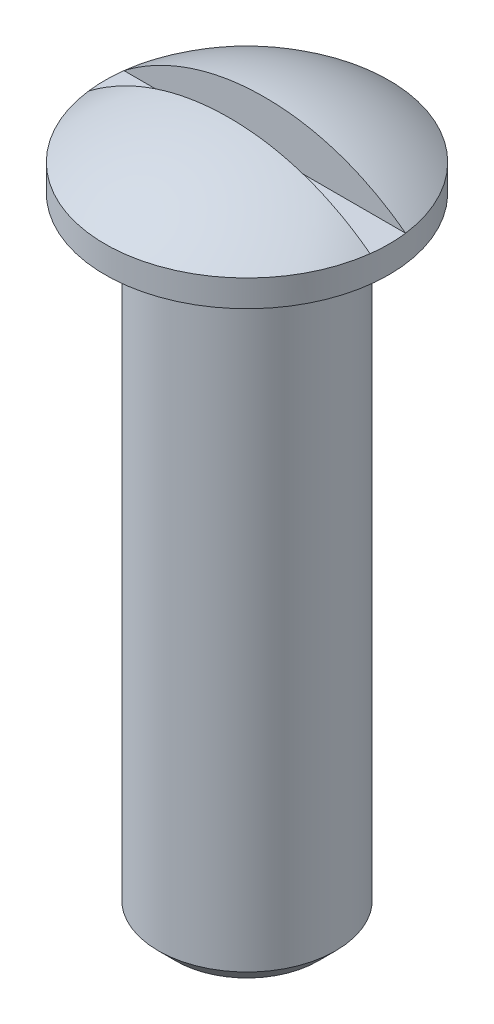
SolidWorks part; units mm, degrees
material "1.0503 (C45)"
ref_plane "Płaszczyzna przednia" through (0, 0, 0) normal (0, 0, 1) x (1, 0, 0)
ref_plane "Płaszczyzna górna" through (0, 0, 0) normal (0, 1, 0) x (1, 0, 0)
ref_plane "Płaszczyzna prawa" through (0, 0, 0) normal (1, 0, 0) x (0, 0, -1)
sketch "Szkic1" plane through (0, 0, 0) normal (0, 0, 1) x (1, 0, 0)
  line L0 (0, 0) -> (0, 39.7) construction
  line L1 (0, 0) -> (5, 0)
  line L2 (5, 0) -> (5, 35.5)
  line L3 (5, 35.5) -> (8, 35.5)
  line L4 (8, 35.5) -> (8, 37)
  line L5 (0, 0) -> (0, 39.7)
  line L6 (5, 7) -> (0, 7) construction
  line L7 (8, 37) -> (8, 39.7) construction
  arc A0 (0, 39.7) -> (8, 37) centre (0.0682, 26.7002) cw
  point P19 (5, 17.75)
  point P20 (0, 39.7)
  dimension "D7" = 13
  dimension "D1" = 35.5
  dimension "D3" = 16
  dimension "D4" = 1.5
  dimension "D5" = 2.7
  dimension "D6" = 28.5
  dimension "D8" = 5
revolve "Obrót1" add sketch "Szkic1" angle 360 about L0
cosmetic thread "Oznaczenie gwintu1" parameters "D1"=9, "D2"=8.344
chamfer "Sfazowanie1" distance 1 angle 45 1 edges at (5, 0, 0)
thread "Gwint2" pitch 1.5 start angle 0, offset 0, length 6, pitch 1.5, diameter 10
ref_plane "Płaszczyzna3" through (5, 1, 0) normal (0, 0, 1) x (1, 0, 0)
sketch "Profil gwintu3" plane through (5, 1, 0) normal (0, 0, 1) x (1, 0, 0)
  line L0 (0, 0) -> (0, 1.5) construction
  line L1 (0, 0) -> (0.8119, 0.4687)
  line L2 (0.8119, 0.4687) -> (0.8119, 0.6562)
  line L3 (0.8119, 0.6562) -> (0, 1.125)
  line L4 (0.8119, 0.5625) -> (0, 0.5625) construction
  line L11 (0, 0) -> (0, 1.125)
  point P2 (0, 0)
  dimension "Pitch" = 1.5
  dimension "Profile_Angle" = 60
  dimension "Profile_Land" = 0.1875
  dimension "Profile_Height" = 0.8119
ref_plane "Płaszczyzna5" through (0, 37, 0) normal (0, 1, 0) x (1, 0, 0)
ref_plane "Płaszczyzna6" through (0, 39.7, 0) normal (0, 1, 0) x (1, 0, 0)
sketch "Szkic5" plane through (0, 37, 0) normal (0, 1, 0) x (1, 0, 0)
  line L1 (-8, 1) -> (8, 1)
  line L2 (-8, 1) -> (-8, -1)
  line L3 (-8, -1) -> (8, -1)
  line L4 (8, 1) -> (8, -1)
  line L5 (-8, 1) -> (8, -1) construction
  line L6 (-8, -1) -> (8, 1) construction
  circle A0 centre (0, 0) radius 8 construction
  point P0 (0, 0)
  point P6 (8, 0)
  dimension "D1" = 2
extrude "Wytnij-wyciągnięcie7" cut sketch "Szkic5" along normal through all
